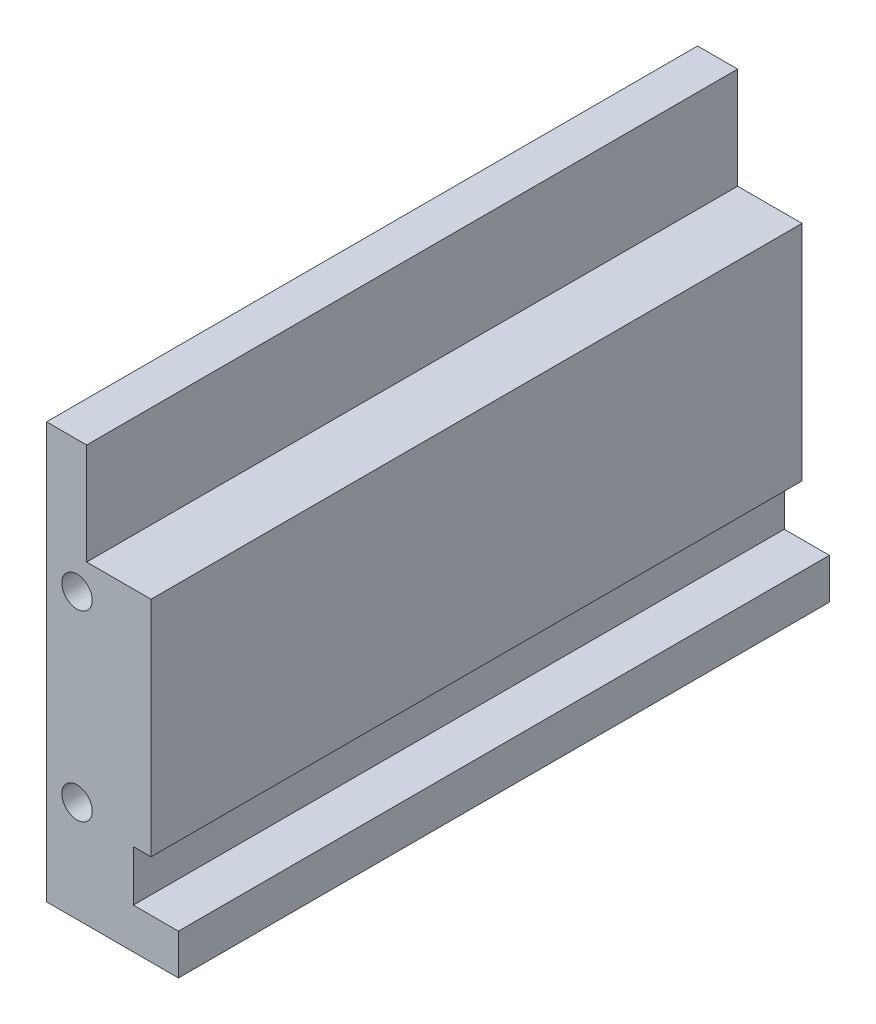
SolidWorks part; units mm, degrees
ref_plane "Front Plane" through (0, 0, 0) normal (0, 0, 1) x (1, 0, 0)
ref_plane "Top Plane" through (0, 0, 0) normal (0, 1, 0) x (1, 0, 0)
ref_plane "Right Plane" through (0, 0, 0) normal (1, 0, 0) x (0, 0, -1)
sketch "Sketch1" plane through (0, 0, 0) normal (0, 0, 1) x (1, 0, 0)
  line L8 (0, 0) -> (0, 41)
  line L9 (0, 41) -> (3.95, 41)
  line L10 (3.95, 41) -> (3.95, 31)
  line L11 (3.95, 31) -> (10.3, 31)
  line L12 (10.3, 31) -> (10.3, 9)
  line L13 (10.3, 9) -> (8.55, 9)
  line L14 (8.55, 9) -> (8.55, 4)
  line L15 (8.55, 4) -> (13, 4)
  line L16 (13, 4) -> (13, 0)
  line L17 (13, 0) -> (0, 0)
  dimension "D1" = 10
  dimension "D2" = 41
  dimension "D3" = 4
  dimension "D4" = 10.3
  dimension "D5" = 13
  dimension "D6" = 9.05
  dimension "D7" = 5
  dimension "D8" = 1.75
extrude "Boss-Extrude1" add sketch "Sketch1" along normal blind 64.2
ref_plane "Plane1" through (0, 0, 32.1) normal (0, 0, 1) x (1, 0, 0)
sketch "Sketch2" plane through (0, 0, 64.2) normal (0, 0, 1) x (1, 0, 0)
  line L0 (3, 41) -> (3, 0) construction
  line L1 (3.95, 41) -> (0, 41) construction
  line L2 (0, 0) -> (13, 0) construction
  line L3 (0, 41) -> (0, 0) construction
  circle A0 centre (3, 28) radius 1.5
  circle A1 centre (3, 10) radius 1.5
  dimension "D2" = 3
  dimension "D1" = 3
  dimension "D3" = 13
  dimension "D4" = 10
extrude "Cut-Extrude1" cut sketch "Sketch2" against normal blind 5
mirror "Mirror1" about plane through (0, 0, 32.1) normal (0, 0, 1) of "Cut-Extrude1"
